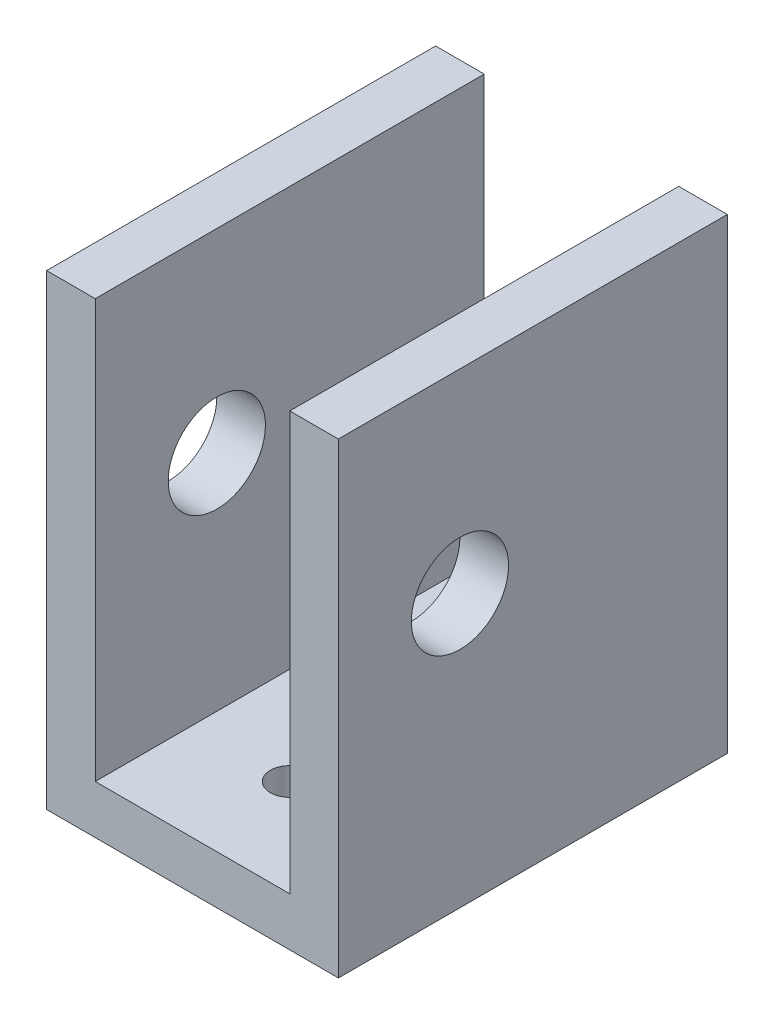
SolidWorks part; units mm, degrees
ref_plane "Front Plane" through (0, 0, 0) normal (0, 0, 1) x (1, 0, 0)
ref_plane "Top Plane" through (0, 0, 0) normal (0, 1, 0) x (1, 0, 0)
ref_plane "Right Plane" through (0, 0, 0) normal (1, 0, 0) x (0, 0, -1)
sketch "Sketch1" plane through (0, 0, 0) normal (0, 0, 1) x (1, 0, 0)
  line L1 (-6.35, -15.875) -> (6.35, -15.875)
  line L2 (-6.35, -15.875) -> (-6.35, 15.875)
  line L3 (-6.35, 15.875) -> (6.35, 15.875)
  line L4 (6.35, -15.875) -> (6.35, 15.875)
  line L5 (-6.35, -15.875) -> (6.35, 15.875) construction
  line L6 (-6.35, 15.875) -> (6.35, -15.875) construction
  line L7 (-9.525, -19.05) -> (9.525, -19.05)
  line L8 (-9.525, -19.05) -> (-9.525, 19.05)
  line L9 (-9.525, 19.05) -> (9.525, 19.05)
  line L10 (9.525, -19.05) -> (9.525, 19.05)
  line L11 (-9.525, -19.05) -> (9.525, 19.05) construction
  line L12 (-9.525, 19.05) -> (9.525, -19.05) construction
  point P0 (0, 0)
  point P5 (0, 0)
  dimension "D1" = 19.05
  dimension "D2" = 38.1
  dimension "D3" = 3.175
  dimension "D4" = 3.175
extrude "Boss-Extrude1" add sketch "Sketch1" along normal mid plane 25.4
sketch "Sketch2" plane through (0, -19.05, 0) normal (0, -1, 0) x (1, 0, 0)
  circle A0 centre (0, 0) radius 2.54
  dimension "D1" = 5.08
extrude "Cut-Extrude1" cut sketch "Sketch2" against normal blind 76.2
sketch "Sketch3" plane through (9.525, 0, 0) normal (1, 0, 0) x (0, 0, -1)
  line L4 (-12.7, -19.05) -> (12.7, -19.05) construction
  circle A0 centre (-4.7625, -1.27) radius 3.175
  dimension "D1" = 6.35
  dimension "D2" = 17.78
  dimension "D3" = 4.7625
extrude "Cut-Extrude2" cut sketch "Sketch3" against normal through all
sketch "Sketch4" plane through (9.525, 0, 0) normal (1, 0, 0) x (0, 0, -1)
  line L0 (-12.7, -19.05) -> (12.7, -19.05) construction
  line L1 (-12.7, 11.43) -> (12.7, 11.43)
  line L2 (-12.7, 11.43) -> (-12.7, 19.05)
  line L3 (-12.7, 19.05) -> (12.7, 19.05)
  line L4 (12.7, 11.43) -> (12.7, 19.05)
  line L5 (12.7, -19.05) -> (12.7, 19.05) construction
  dimension "D1" = 30.48
extrude "Cut-Extrude3" cut sketch "Sketch4" against normal through all
sketch "Sketch5" plane through (0, -19.05, 0) normal (0, -1, 0) x (1, 0, 0)
  line L0 (-9.525, -12.7) -> (9.525, -12.7) construction
  line L1 (-9.525, 12.7) -> (9.525, 12.7) construction
  circle A0 centre (0, -6.35) radius 1.27
  circle A1 centre (0, 6.35) radius 1.27
  dimension "D1" = 2.54
  dimension "D2" = 6.35
  dimension "D3" = 6.35
extrude "Cut-Extrude4" cut sketch "Sketch5" against normal through all
